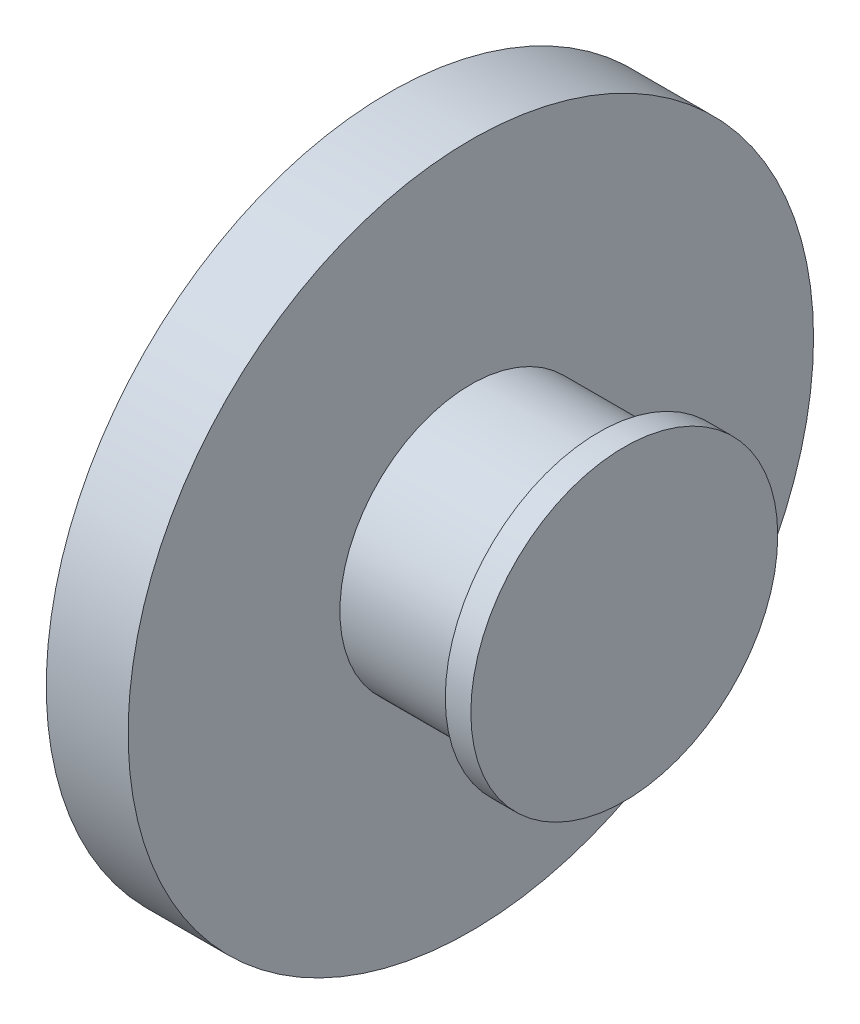
SolidWorks part; units mm, degrees
ref_plane "Front Plane" through (0, 0, 0) normal (0, 0, 1) x (1, 0, 0)
ref_plane "Top Plane" through (0, 0, 0) normal (0, 1, 0) x (1, 0, 0)
ref_plane "Right Plane" through (0, 0, 0) normal (1, 0, 0) x (0, 0, -1)
sketch "Sketch2" plane through (0, 0, 0) normal (1, 0, 0) x (0, 0, -1)
  circle A0 centre (0, 0) radius 17.9
  circle A1 centre (0, 0) radius 12.8
  circle A2 centre (0, 0) radius 33.5
  dimension "D1" = 35.8
  dimension "D2" = 25.6
  dimension "D3" = 67
extrude "Boss-Extrude1" add sketch "Sketch2" along normal blind 8 contours A2
sketch "Sketch7" plane through (8, 0, 0) normal (1, 0, 0) x (0, 0, -1)
  circle A0 centre (0, 0) radius 12.8
  dimension "D1" = 25.6
extrude "Boss-Extrude2" add sketch "Sketch7" along normal blind 12.5
sketch "Sketch8" plane through (20.5, 0, 0) normal (1, 0, 0) x (0, 0, -1)
  circle A0 centre (0, 0) radius 15
  dimension "D1" = 30
extrude "Boss-Extrude3" add sketch "Sketch8" along normal blind 2.5
sketch "Sketch10" plane through (0, 0, 0) normal (-1, 0, 0) x (0, 0, 1)
  line L0 (-4, -27.2039) -> (-6.5, -6.5)
  line L1 (-6.5, -6.5) -> (-27.2039, -4)
  line L2 (-27.2039, 4) -> (-6.5, 6.5)
  line L3 (-6.5, 6.5) -> (-4, 27.2039)
  line L4 (4, 27.2039) -> (6.5, 6.5)
  line L5 (6.5, 6.5) -> (27.2039, 4)
  line L6 (27.2039, -4) -> (6.5, -6.5)
  line L7 (6.5, -6.5) -> (4, -27.2039)
  line L8 (-6.5, 6.5) -> (6.5, 6.5) construction
  line L9 (6.5, 6.5) -> (6.5, -6.5) construction
  line L10 (6.5, -6.5) -> (-6.5, -6.5) construction
  line L11 (-6.5, 6.5) -> (-6.5, -6.5) construction
  line L12 (0, 0) -> (-6.5, 0) construction
  line L13 (0, 0) -> (0, -6.5) construction
  line L14 (-26.7209, 0) -> (-6.5, 0) construction
  line L15 (0, -26.7209) -> (0, -6.5) construction
  line L16 (26.7209, 0) -> (6.5, 0) construction
  line L17 (0, 6.5) -> (0, 26.7209) construction
  line L18 (-30.75, 0) -> (-26.7209, 0) construction
  line L19 (26.7209, 0) -> (30.75, 0) construction
  arc A0 (-27.2039, 4) -> (-27.2039, -4) centre (-26.7209, 0) ccw
  arc A1 (27.2039, 4) -> (27.2039, -4) centre (26.7209, 0) cw
  arc A2 (-4, 27.2039) -> (4, 27.2039) centre (0, 26.7209) cw
  arc A3 (4, -27.2039) -> (-4, -27.2039) centre (0, -26.7209) cw
  dimension "D1" = 61.5
  dimension "D2" = 13
  dimension "D3" = 8
extrude "Cut-Extrude1" cut sketch "Sketch10" against normal blind 5.5
sketch "Sketch11" plane through (5.5, 0, 0) normal (-1, 0, 0) x (0, 0, 1)
  circle A0 centre (0, 0) radius 6
  dimension "D1" = 12
extrude "Cut-Extrude2" cut sketch "Sketch11" against normal blind 3.2
